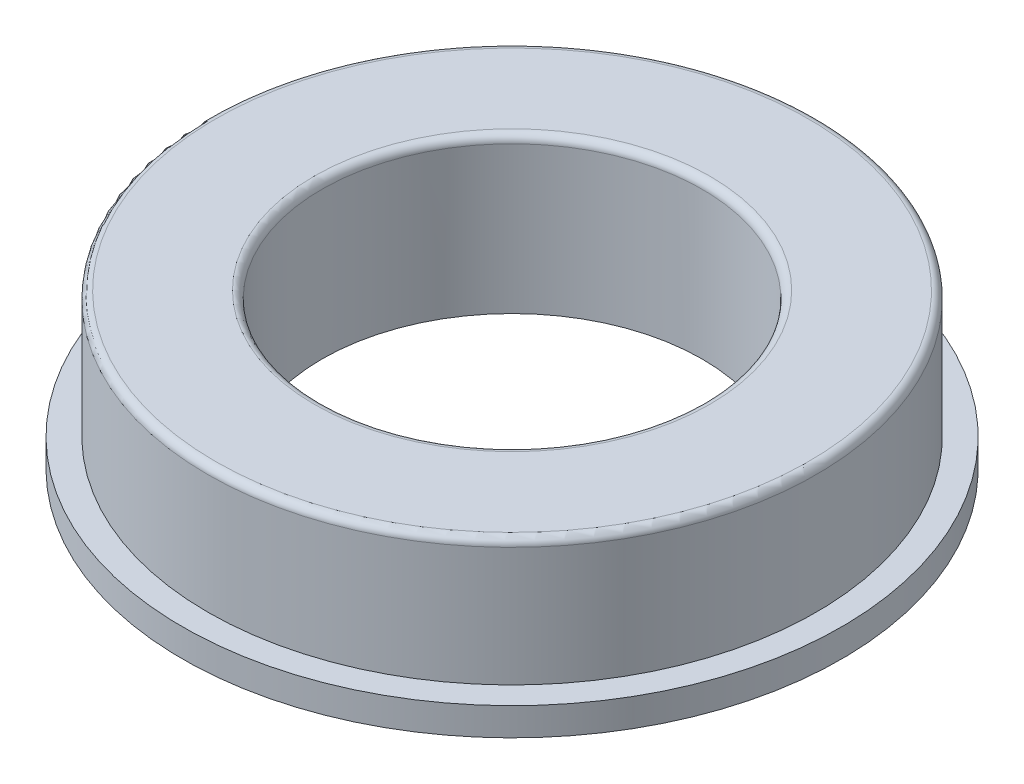
SolidWorks part; units mm, degrees
ref_plane "前视基准面" through (0, 0, 0) normal (0, 0, 1) x (1, 0, 0)
ref_plane "上视基准面" through (0, 0, 0) normal (0, 1, 0) x (1, 0, 0)
ref_plane "右视基准面" through (0, 0, 0) normal (1, 0, 0) x (0, 0, -1)
ref_plane "基准面1" through (0, 0, 0) normal (0, 0, -1) x (-1, 0, 0)
sketch "草图1" plane through (0, 0, 0) normal (0, 0, -1) x (-1, 0, 0)
  line L0 (-11.7, 0) -> (-7.8, 0)
  line L1 (-7.5, 0.3) -> (-7.5, 4.7)
  line L2 (-7.8, 5) -> (-11.7, 5)
  line L3 (-12, 4.7) -> (-12, 0.3)
  line L4 (0, -0.0013) -> (0, 5.0013) construction
  line L5 (-11.7, 0) -> (-12, 0)
  line L6 (-12, 0) -> (-12, 0.3)
  line L7 (-7.5, 0.3) -> (-7.5, 0)
  line L8 (-7.5, 0) -> (-7.8, 0)
  arc A2 (-7.5, 4.7) -> (-7.8, 5) centre (-7.8, 4.7) ccw
  arc A3 (-11.7, 5) -> (-12, 4.7) centre (-11.7, 4.7) ccw
revolve "旋转1" add sketch "草图1" angle 360 about L4
sketch "草图2" plane through (0, 0, 0) normal (0, -1, 0) x (1, 0, 0)
  circle A0 centre (0, 0) radius 13
  dimension "D1" = 26
extrude "凸台-拉伸1" add sketch "草图2" along normal blind 1.1
sketch "草图3" plane through (0, 0, 0) normal (0, 1, 0) x (1, 0, 0)
  circle A0 centre (0, 0) radius 7.5
extrude "切除-拉伸1" cut sketch "草图3" against normal up to next
